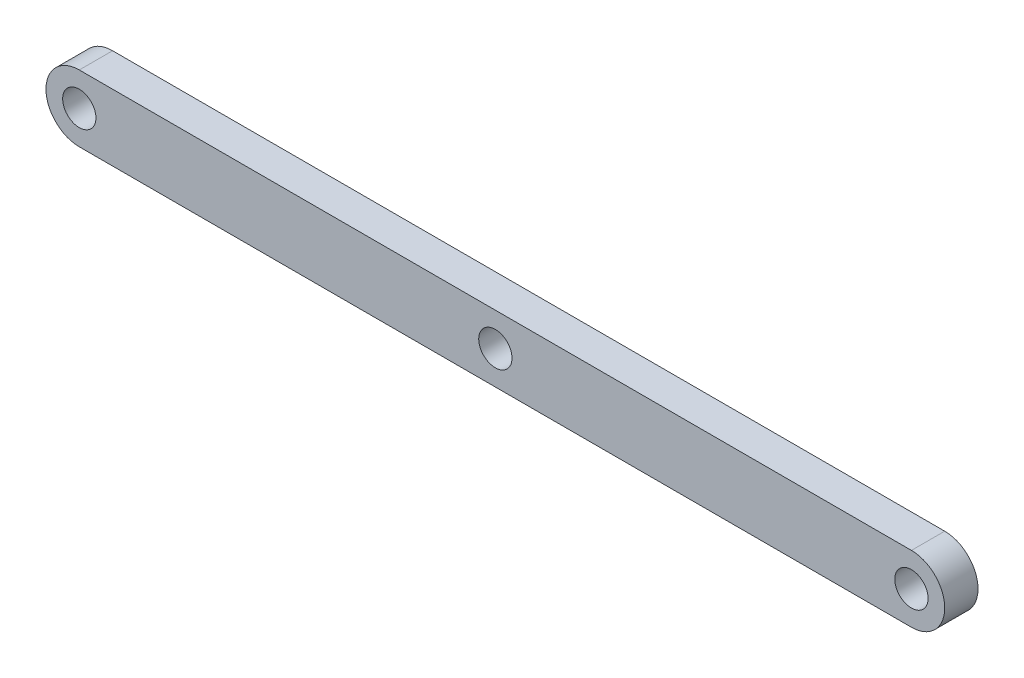
SolidWorks part; units mm, degrees
ref_plane "Front Plane" through (0, 0, 0) normal (0, 0, 1) x (1, 0, 0)
ref_plane "Top Plane" through (0, 0, 0) normal (0, 1, 0) x (1, 0, 0)
ref_plane "Right Plane" through (0, 0, 0) normal (1, 0, 0) x (0, 0, -1)
sketch "Sketch1" plane through (0, 0, 0) normal (0, 0, 1) x (1, 0, 0)
  line L0 (-125, 0) -> (125, 0) construction
  line L1 (-125, 10) -> (125, 10)
  line L2 (-125, -10) -> (125, -10)
  arc A0 (-125, 10) -> (-125, -10) centre (-125, 0) ccw
  arc A1 (125, -10) -> (125, 10) centre (125, 0) ccw
  circle A2 centre (-125, 0) radius 5
  circle A3 centre (125, 0) radius 5
  point P3 (0, 0)
  dimension "D4" = 10
  dimension "D5" = 10
  dimension "D1" = 20
  dimension "D2" = 250
  dimension "D3" = 0
extrude "Boss-Extrude1" add sketch "Sketch1" along normal mid plane 10
sketch "Sketch2" plane through (0, 0, 0) normal (0, 0, 1) x (1, 0, 0)
  circle A0 centre (0, 0) radius 5
  dimension "D1" = 10
extrude "Cut-Extrude2" cut sketch "Sketch2" against normal mid plane 10 contours A0
